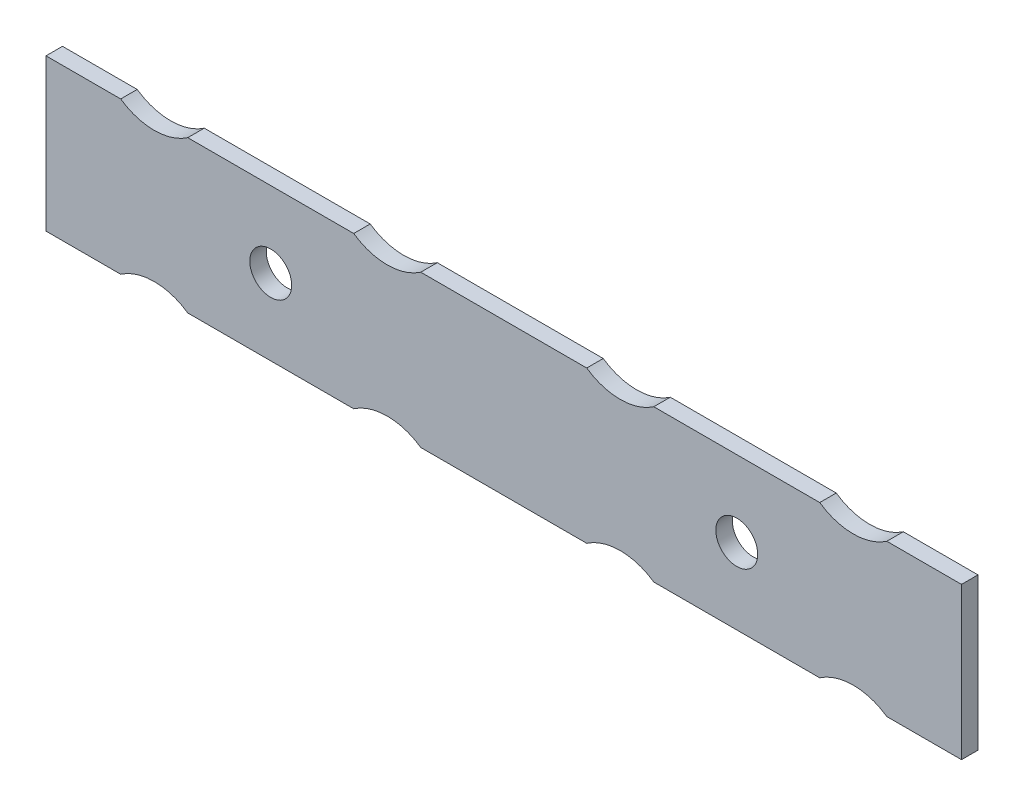
SolidWorks part; units mm, degrees
material "3003 Alloy"
ref_plane "X-Y Datum" through (0, 0, 0) normal (0, 0, 1) x (1, 0, 0)
ref_plane "X-Z Datum" through (0, 0, 0) normal (0, 1, 0) x (1, 0, 0)
ref_plane "Y-Z Datum" through (0, 0, 0) normal (1, 0, 0) x (0, 0, -1)
sketch "Sketch1" plane through (0, 0, 0) normal (0, 0, 1) x (1, 0, 0)
  line L0 (-3.2531, 4.7) -> (-10.5, 4.7) construction
  line L1 (-10.5, 0) -> (-10.5, 4.7) construction
  line L2 (78.318, 24.13) -> (78.318, 15.2474) construction
  line L3 (3.2531, 19.43) -> (19.3529, 19.43) construction
  line L4 (3.2531, 19.43) -> (19.3529, 19.43)
  line L5 (-10.5, 4.7) -> (-3.2531, 4.7)
  line L6 (-10.5, 4.7) -> (-10.5, 19.43)
  line L7 (-10.5, 19.43) -> (-3.2531, 19.43)
  line L8 (78.318, 4.7) -> (78.318, 19.43)
  line L9 (71.0711, 19.43) -> (78.318, 19.43) construction
  line L10 (71.0711, 19.43) -> (78.318, 19.43)
  line L11 (48.4651, 19.43) -> (64.5649, 19.43) construction
  line L12 (48.4651, 19.43) -> (64.5649, 19.43)
  line L13 (25.8591, 19.43) -> (41.9589, 19.43) construction
  line L14 (25.8591, 19.43) -> (41.9589, 19.43)
  line L15 (3.2531, 4.7) -> (19.3529, 4.7)
  line L16 (25.8591, 4.7) -> (41.9589, 4.7)
  line L17 (48.4651, 4.7) -> (64.5649, 4.7)
  line L18 (71.0711, 4.7) -> (78.318, 4.7)
  circle A0 centre (0, 0) radius 4.7 construction
  circle A1 centre (0, 24.13) radius 4.7 construction
  arc A2 (-3.2531, 19.43) -> (3.2531, 19.43) centre (0, 24.13) ccw
  arc A3 (3.2531, 4.7) -> (-3.2531, 4.7) centre (0, 0) ccw
  circle A6 centre (11.303, 12.065) radius 2.032
  circle A7 centre (56.515, 12.065) radius 2.032
  arc A8 (19.3529, 19.43) -> (25.8591, 19.43) centre (22.606, 24.13) ccw
  arc A9 (25.8591, 4.7) -> (19.3529, 4.7) centre (22.606, 0) ccw
  arc A10 (41.9589, 19.43) -> (48.4651, 19.43) centre (45.212, 24.13) ccw
  arc A11 (48.4651, 4.7) -> (41.9589, 4.7) centre (45.212, 0) ccw
  arc A12 (64.5649, 19.43) -> (71.0711, 19.43) centre (67.818, 24.13) ccw
  arc A13 (71.0711, 4.7) -> (64.5649, 4.7) centre (67.818, 0) ccw
  circle A14 centre (0, 24.13) radius 5.716 construction
  circle A15 centre (0, 0) radius 5.716 construction
  dimension "D1" = 1.016
  dimension "D2" = 4
extrude "Boss-Extrude1" add sketch "Sketch1" along normal blind 1.6
